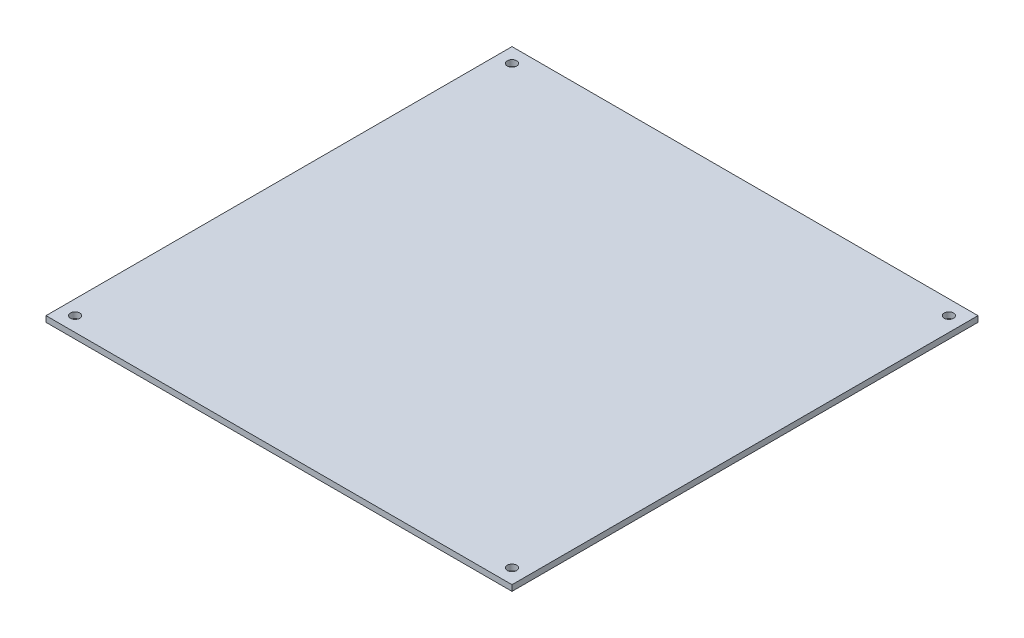
SolidWorks part; units mm, degrees
ref_plane "Front Plane" through (0, 0, 0) normal (0, 0, 1) x (1, 0, 0)
ref_plane "Top Plane" through (0, 0, 0) normal (0, 1, 0) x (1, 0, 0)
ref_plane "Right Plane" through (0, 0, 0) normal (1, 0, 0) x (0, 0, -1)
sketch "Sketch1" plane through (0, 0, 0) normal (0, 1, 0) x (1, 0, 0)
  line L1 (-200, -200) -> (200, -200)
  line L2 (-200, -200) -> (-200, 200)
  line L3 (-200, 200) -> (200, 200)
  line L4 (200, -200) -> (200, 200)
  line L5 (-200, -200) -> (200, 200) construction
  line L6 (-200, 200) -> (200, -200) construction
  point P0 (0, 0)
  dimension "D1" = 400
  dimension "D2" = 400
extrude "Boss-Extrude1" add sketch "Sketch1" along normal blind 5
sketch "Sketch2" plane through (0, 5, 0) normal (0, 1, 0) x (1, 0, 0)
  line L0 (200, 200) -> (-200, 200) construction
  line L3 (-200, 200) -> (-200, -200) construction
  line L5 (0, 200) -> (0, -200) construction
  line L7 (-200, -200) -> (200, -200) construction
  line L12 (-200, 0) -> (200, 0) construction
  line L13 (200, -200) -> (200, 200) construction
  circle A2 centre (-187.5, 187.5) radius 4
  circle A3 centre (187.5, 187.5) radius 4
  circle A4 centre (-187.5, -187.5) radius 4
  circle A5 centre (187.5, -187.5) radius 4
  point P17 (0, 0)
  point P18 (0, 0)
  dimension "D1" = 12.5
  dimension "D2" = 12.5
  dimension "D3" = 8
extrude "Cut-Extrude1" cut sketch "Sketch2" against normal through all
